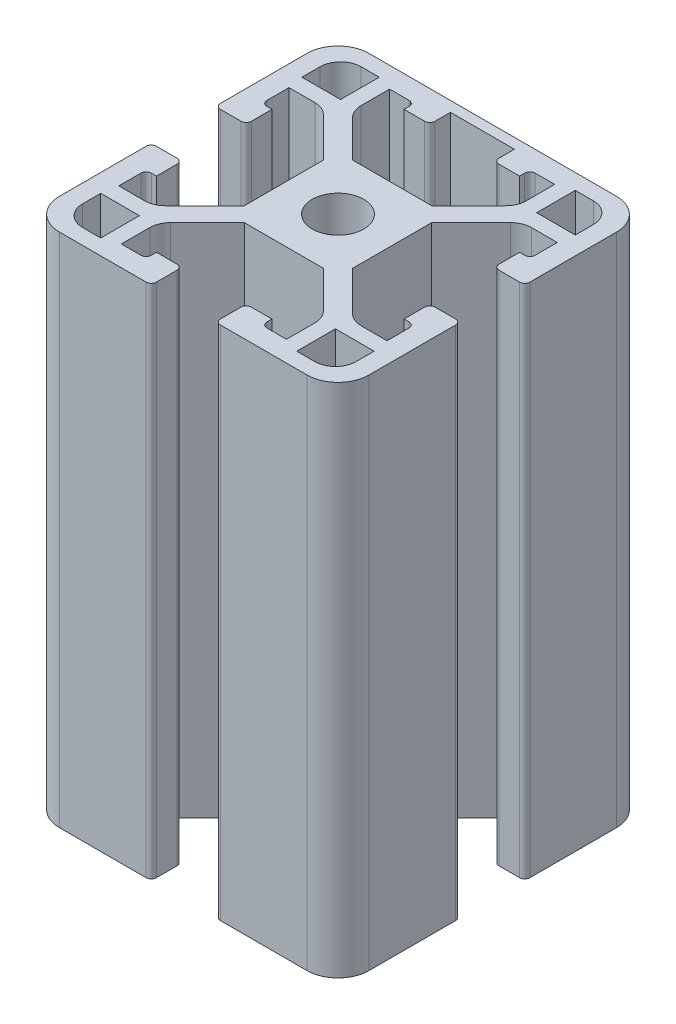
SolidWorks part; units mm, degrees
ref_plane "Front Plane" through (0, 0, 0) normal (0, 0, 1) x (1, 0, 0)
ref_plane "Top Plane" through (0, 0, 0) normal (0, 1, 0) x (1, 0, 0)
ref_plane "Right Plane" through (0, 0, 0) normal (1, 0, 0) x (0, 0, -1)
sketch "Sketch2" plane through (0, 0, 0) normal (0, 1, 0) x (1, 0, 0)
  line L0 (3.6, -15) -> (12, -15)
  line L1 (15, -12) -> (15, -3.6)
  line L2 (14.5, -3.1) -> (12.5, -3.1)
  line L3 (12, -3.6) -> (12, -5.6)
  line L4 (12, -5.6) -> (12.5, -5.6)
  line L5 (13, -6.1) -> (13, -8.25)
  line L6 (13, -8.25) -> (10.4926, -8.25)
  line L7 (9.0784, -7.6642) -> (5.25, -3.8358)
  line L9 (3.8358, -5.25) -> (7.4142, -8.8284)
  line L10 (8, -10.2426) -> (8, -13)
  line L11 (8, -13) -> (6.1, -13)
  line L12 (5.6, -12.5) -> (5.6, -12)
  line L13 (5.6, -12) -> (3.6, -12)
  line L14 (3.1, -12.5) -> (3.1, -14.5)
  line L15 (0, 0) -> (0, 2.5) construction
  line L16 (-3.8358, 5.25) -> (3.8358, 5.25)
  line L17 (-5.25, 3.8358) -> (-5.25, -3.8358)
  line L18 (-3.8358, -5.25) -> (3.8358, -5.25)
  line L19 (5.25, 3.8358) -> (5.25, -3.8358)
  line L20 (-1.7678, 1.7678) -> (8.7215, -8.7215) construction
  line L21 (-1.7678, -1.7678) -> (1.7678, 1.7678) construction
  line L22 (9.5, -9.75) -> (13.25, -9.75)
  line L23 (9.5, -9.75) -> (9.5, -13.5)
  line L24 (9.5, -13.5) -> (11.25, -13.5)
  line L25 (13.25, -9.75) -> (13.25, -11.5)
  line L26 (0, 0) -> (-2.5, 0) construction
  line L27 (-3.1, -12.5) -> (-3.1, -14.5)
  line L28 (-5.6, -12) -> (-3.6, -12)
  line L29 (-5.6, -12.5) -> (-5.6, -12)
  line L30 (-13.25, -9.75) -> (-13.25, -11.5)
  line L31 (-9.5, -13.5) -> (-11.25, -13.5)
  line L32 (-9.5, -9.75) -> (-9.5, -13.5)
  line L33 (-9.5, -9.75) -> (-13.25, -9.75)
  line L34 (-8, -13) -> (-6.1, -13)
  line L35 (-8, -10.2426) -> (-8, -13)
  line L36 (-3.8358, -5.25) -> (-7.4142, -8.8284)
  line L37 (-9.0784, -7.6642) -> (-5.25, -3.8358)
  line L38 (-13, -8.25) -> (-10.4926, -8.25)
  line L39 (-13, -6.1) -> (-13, -8.25)
  line L40 (-12, -5.6) -> (-12.5, -5.6)
  line L41 (-12, -3.6) -> (-12, -5.6)
  line L42 (-14.5, -3.1) -> (-12.5, -3.1)
  line L43 (-15, -12) -> (-15, -3.6)
  line L44 (-3.6, -15) -> (-12, -15)
  line L45 (3.1, 12.5) -> (3.1, 14)
  line L46 (5.6, 12) -> (3.6, 12)
  line L47 (5.6, 12.5) -> (5.6, 12)
  line L48 (-5.6, 12.5) -> (-5.6, 12)
  line L49 (-5.6, 12) -> (-3.6, 12)
  line L50 (-3.1, 12.5) -> (-3.1, 14)
  line L52 (-8, 13) -> (-6.1, 13)
  line L53 (-3.8358, 5.25) -> (-7.4142, 8.8284)
  line L54 (-9.0784, 7.6642) -> (-5.25, 3.8358)
  line L55 (-15, 12) -> (-15, 3.6)
  line L56 (-14.5, 3.1) -> (-12.5, 3.1)
  line L57 (-12, 3.6) -> (-12, 5.6)
  line L58 (-12, 5.6) -> (-12.5, 5.6)
  line L59 (-13, 6.1) -> (-13, 8.25)
  line L60 (-13, 8.25) -> (-10.4926, 8.25)
  line L61 (-8, 10.2426) -> (-8, 13)
  line L62 (-9.5, 9.75) -> (-13.25, 9.75)
  line L63 (-9.5, 9.75) -> (-9.5, 13.5)
  line L64 (-9.5, 13.5) -> (-11.25, 13.5)
  line L65 (-13.25, 9.75) -> (-13.25, 11.5)
  line L66 (13.25, 9.75) -> (13.25, 11.5)
  line L67 (9.5, 13.5) -> (11.25, 13.5)
  line L68 (9.5, 9.75) -> (9.5, 13.5)
  line L69 (9.5, 9.75) -> (13.25, 9.75)
  line L70 (8, 13) -> (6.1, 13)
  line L71 (8, 10.2426) -> (8, 13)
  line L72 (3.8358, 5.25) -> (7.4142, 8.8284)
  line L73 (9.0784, 7.6642) -> (5.25, 3.8358)
  line L74 (13, 8.25) -> (10.4926, 8.25)
  line L75 (13, 6.1) -> (13, 8.25)
  line L76 (12, 5.6) -> (12.5, 5.6)
  line L77 (12, 3.6) -> (12, 5.6)
  line L78 (14.5, 3.1) -> (12.5, 3.1)
  line L79 (15, 12) -> (15, 3.6)
  line L81 (0, 5.25) -> (0, 9.0083) construction
  line L82 (-5.25, 0) -> (-10.2369, 0) construction
  line L83 (12, 15) -> (-12, 15)
  line L86 (-3.1, 14) -> (3.1, 14)
  circle A0 centre (0, 0) radius 2.5
  arc A1 (7.4142, -8.8284) -> (8, -10.2426) centre (6, -10.2426) cw
  arc A2 (10.4926, -8.25) -> (9.0784, -7.6642) centre (10.4926, -6.25) cw
  arc A5 (15, -3.6) -> (14.5, -3.1) centre (14.5, -3.6) ccw
  arc A6 (12.5, -3.1) -> (12, -3.6) centre (12.5, -3.6) ccw
  arc A7 (12.5, -5.6) -> (13, -6.1) centre (12.5, -6.1) cw
  arc A8 (6.1, -13) -> (5.6, -12.5) centre (6.1, -12.5) cw
  arc A9 (3.6, -15) -> (3.1, -14.5) centre (3.6, -14.5) cw
  arc A10 (3.6, -12) -> (3.1, -12.5) centre (3.6, -12.5) ccw
  arc A11 (12, -15) -> (15, -12) centre (12, -12) ccw
  arc A12 (11.25, -13.5) -> (13.25, -11.5) centre (11.25, -11.5) ccw
  arc A13 (-3.6, -15) -> (-3.1, -14.5) centre (-3.6, -14.5) ccw
  arc A14 (-3.6, -12) -> (-3.1, -12.5) centre (-3.6, -12.5) cw
  arc A15 (-6.1, -13) -> (-5.6, -12.5) centre (-6.1, -12.5) ccw
  arc A16 (-11.25, -13.5) -> (-13.25, -11.5) centre (-11.25, -11.5) cw
  arc A17 (-12, -15) -> (-15, -12) centre (-12, -12) cw
  arc A18 (-12.5, -5.6) -> (-13, -6.1) centre (-12.5, -6.1) ccw
  arc A19 (-12.5, -3.1) -> (-12, -3.6) centre (-12.5, -3.6) cw
  arc A20 (-15, -3.6) -> (-14.5, -3.1) centre (-14.5, -3.6) cw
  arc A21 (-10.4926, -8.25) -> (-9.0784, -7.6642) centre (-10.4926, -6.25) ccw
  arc A22 (-7.4142, -8.8284) -> (-8, -10.2426) centre (-6, -10.2426) ccw
  arc A24 (3.6, 12) -> (3.1, 12.5) centre (3.6, 12.5) cw
  arc A25 (6.1, 13) -> (5.6, 12.5) centre (6.1, 12.5) ccw
  arc A26 (-3.6, 12) -> (-3.1, 12.5) centre (-3.6, 12.5) ccw
  arc A28 (-6.1, 13) -> (-5.6, 12.5) centre (-6.1, 12.5) cw
  arc A29 (-7.4142, 8.8284) -> (-8, 10.2426) centre (-6, 10.2426) cw
  arc A30 (-10.4926, 8.25) -> (-9.0784, 7.6642) centre (-10.4926, 6.25) cw
  arc A31 (-15, 3.6) -> (-14.5, 3.1) centre (-14.5, 3.6) ccw
  arc A32 (-12.5, 3.1) -> (-12, 3.6) centre (-12.5, 3.6) ccw
  arc A33 (-12.5, 5.6) -> (-13, 6.1) centre (-12.5, 6.1) cw
  arc A34 (-12, 15) -> (-15, 12) centre (-12, 12) ccw
  arc A35 (-11.25, 13.5) -> (-13.25, 11.5) centre (-11.25, 11.5) ccw
  arc A36 (11.25, 13.5) -> (13.25, 11.5) centre (11.25, 11.5) cw
  arc A37 (12, 15) -> (15, 12) centre (12, 12) cw
  arc A38 (12.5, 5.6) -> (13, 6.1) centre (12.5, 6.1) ccw
  arc A39 (12.5, 3.1) -> (12, 3.6) centre (12.5, 3.6) cw
  arc A40 (15, 3.6) -> (14.5, 3.1) centre (14.5, 3.6) cw
  arc A41 (10.4926, 8.25) -> (9.0784, 7.6642) centre (10.4926, 6.25) ccw
  arc A42 (7.4142, 8.8284) -> (8, 10.2426) centre (6, 10.2426) ccw
  point P34 (13.25, -13.5)
  point P37 (5.6, -12.25)
  point P40 (15, -3.1)
  point P43 (12, -3.1)
  point P50 (3.1, -15)
  point P53 (3.1, -12)
  point P54 (3.1, -13.5)
  point P58 (-3.1, -13.5)
  point P62 (-3.1, -12)
  point P64 (-5.6, -12.25)
  point P97 (-12, -3.1)
  point P98 (-15, -3.1)
  point P99 (-13.25, -13.5)
  point P149 (-13.25, 13.5)
  point P150 (-15, 3.1)
  point P151 (-12, 3.1)
  point P181 (12, 3.1)
  point P182 (15, 3.1)
  point P183 (13.25, 13.5)
  dimension "D1" = 5
  dimension "D22" = 2
  dimension "D23" = 0.5
  dimension "D24" = 3
  dimension "D25" = 2
  dimension "D30" = 7.6716
  dimension "D3" = 30
  dimension "D4" = 30
  dimension "D5" = 1
  dimension "D6" = 3.1
  dimension "D7" = 3
  dimension "D8" = 2
  dimension "D9" = 9.75
  dimension "D10" = 9.75
  dimension "D11" = 3
  dimension "D12" = 2
  dimension "D13" = 6.75
  dimension "D14" = 7
  dimension "D15" = 3.75
  dimension "D16" = 3.75
  dimension "D17" = 1.5
  dimension "D18" = 1.5
  dimension "D19" = 3.1
  dimension "D20" = 2.5
  dimension "D21" = 2.5
  dimension "D26" = 1
  dimension "D27" = 10.5
  dimension "D28" = 10.5
  dimension "D29" = 2
  dimension "D31" = 5.4142
  dimension "D32" = 45
  dimension "D33" = 90
extrude "Boss-Extrude1" add sketch "Sketch2" along normal blind 50
